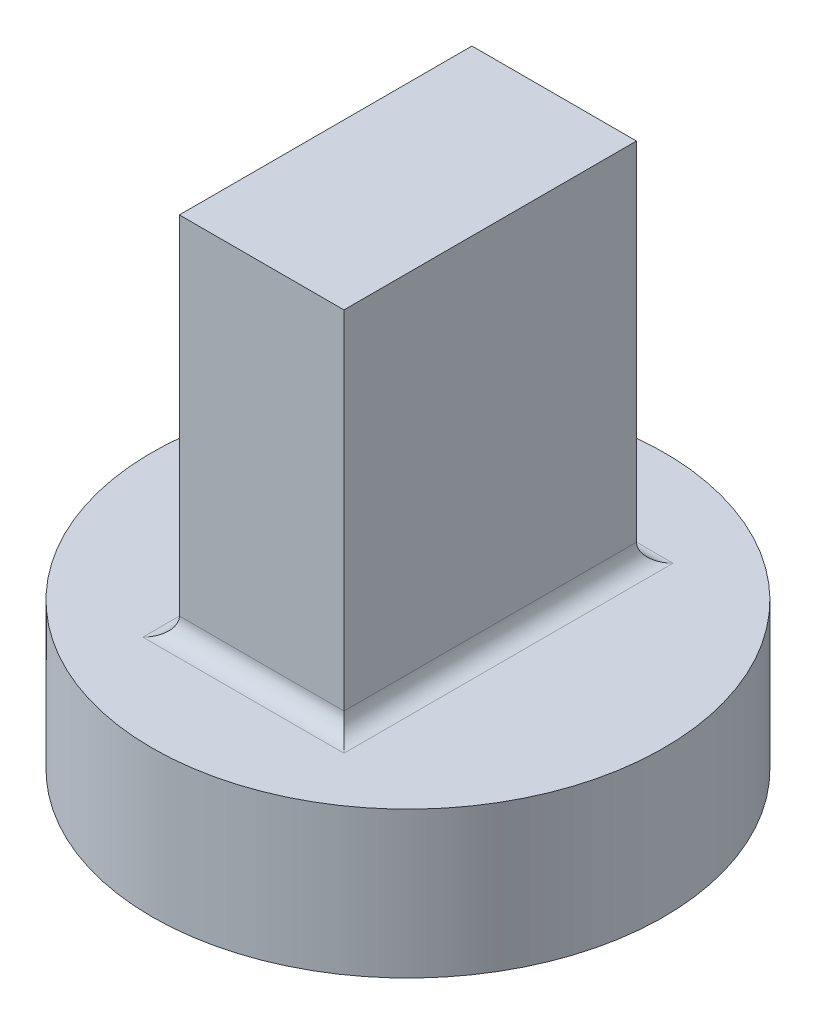
SolidWorks part; units mm, degrees
ref_plane "Front Plane" through (0, 0, 0) normal (0, 0, 1) x (1, 0, 0)
ref_plane "Top Plane" through (0, 0, 0) normal (0, 1, 0) x (1, 0, 0)
ref_plane "Right Plane" through (0, 0, 0) normal (1, 0, 0) x (0, 0, -1)
sketch "Sketch1" plane through (0, 0, 0) normal (0, 1, 0) x (1, 0, 0)
  circle A0 centre (0, 0) radius 7
  dimension "D1" = 14
extrude "Boss-Extrude1" add sketch "Sketch1" along normal blind 4
sketch "Sketch2" plane through (0, 4, 0) normal (0, 1, 0) x (1, 0, 0)
  line L1 (-2.25, 4) -> (2.25, 4)
  line L2 (-2.25, 4) -> (-2.25, -4)
  line L3 (-2.25, -4) -> (2.25, -4)
  line L4 (2.25, 4) -> (2.25, -4)
  dimension "D1" = 4.5
  dimension "D2" = 8
  dimension "D3" = 4
  dimension "D4" = 2.25
extrude "Boss-Extrude2" add sketch "Sketch2" along normal blind 10
fillet "Fillet2" radius 0.5 4 edges at (-2.25, 4, 0) (0, 4, 4) (2.25, 4, 0) (0, 4, -4)
